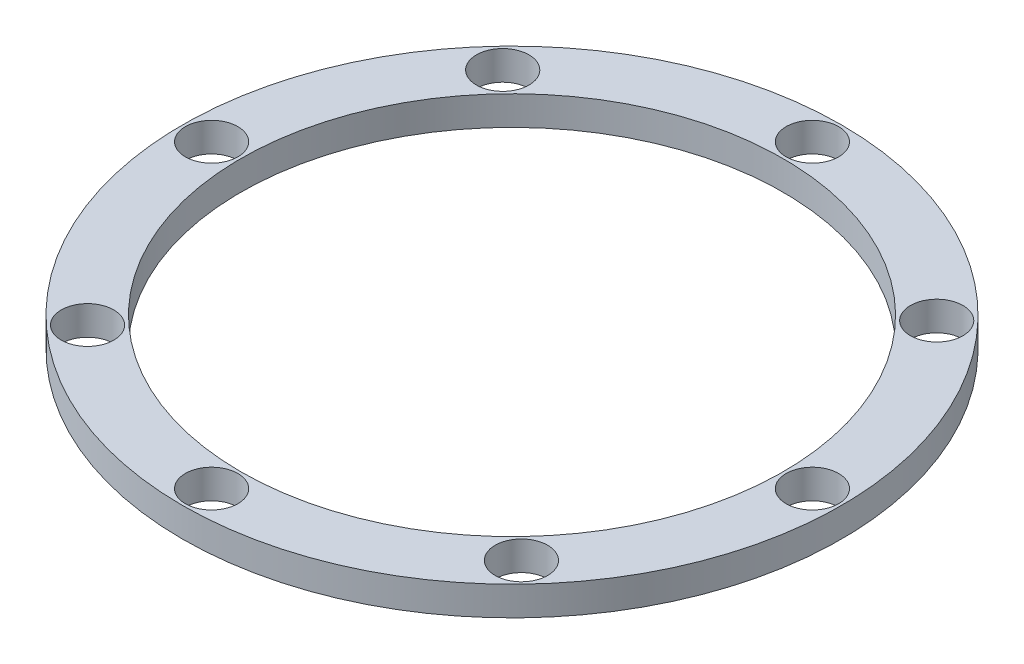
SolidWorks part; units mm, degrees
ref_plane "Front Plane" through (0, 0, 0) normal (0, 0, 1) x (1, 0, 0)
ref_plane "Top Plane" through (0, 0, 0) normal (0, 1, 0) x (1, 0, 0)
ref_plane "Right Plane" through (0, 0, 0) normal (1, 0, 0) x (0, 0, -1)
sketch "Sketch1" plane through (0, 0, 0) normal (0, 1, 0) x (1, 0, 0)
  line L0 (0, 56.5) -> (0, 46.5)
  line L1 (0, -46.5) -> (0, -56.5)
  line L2 (-46.5, 0) -> (-56.5, 0)
  line L3 (46.5, 0) -> (56.5, 0)
  line L4 (-33.5913, 32.154) -> (-40.8152, 39.0688)
  line L5 (33.6019, -32.1429) -> (40.8281, -39.0553)
  line L6 (-31.5315, -34.1763) -> (-38.3124, -41.526)
  line L7 (33.6019, 32.1429) -> (40.8281, 39.0553)
  circle A0 centre (0, 0) radius 46.5
  circle A1 centre (0, 0) radius 56.5
  circle A2 centre (-37.2032, 35.6114) radius 4.5
  circle A3 centre (0, 51.5) radius 4.5
  circle A4 centre (37.215, 35.5991) radius 4.5
  circle A5 centre (-51.5, 0) radius 4.5
  circle A6 centre (-34.9219, -37.8511) radius 4.5
  circle A7 centre (0, -51.5) radius 4.5
  circle A9 centre (51.5, 0) radius 4.5
  circle A10 centre (37.215, -35.5991) radius 4.5
  dimension "D1" = 93
  dimension "D2" = 113
  dimension "D3" = 9
  dimension "D4" = 9
  dimension "D5" = 9
  dimension "D6" = 9
  dimension "D7" = 9
  dimension "D8" = 9
  dimension "D9" = 9
  dimension "D10" = 9
extrude "Boss-Extrude1" add sketch "Sketch1" along normal blind 5 contours A10 L5 A0 L1 A7 A1 | A10 L5 A1 L3 A9 A0 | A9 L3 A1 L7 A4 A0 | A4 L7 A1 L0 A3 A0 | A3 L0 A1 L4 A2 A0 | A5 L2 A0 L4 A2 A1 | A6 L6 A0 L2 A5 A1 | A7 L1 A0 L6 A6 A1
